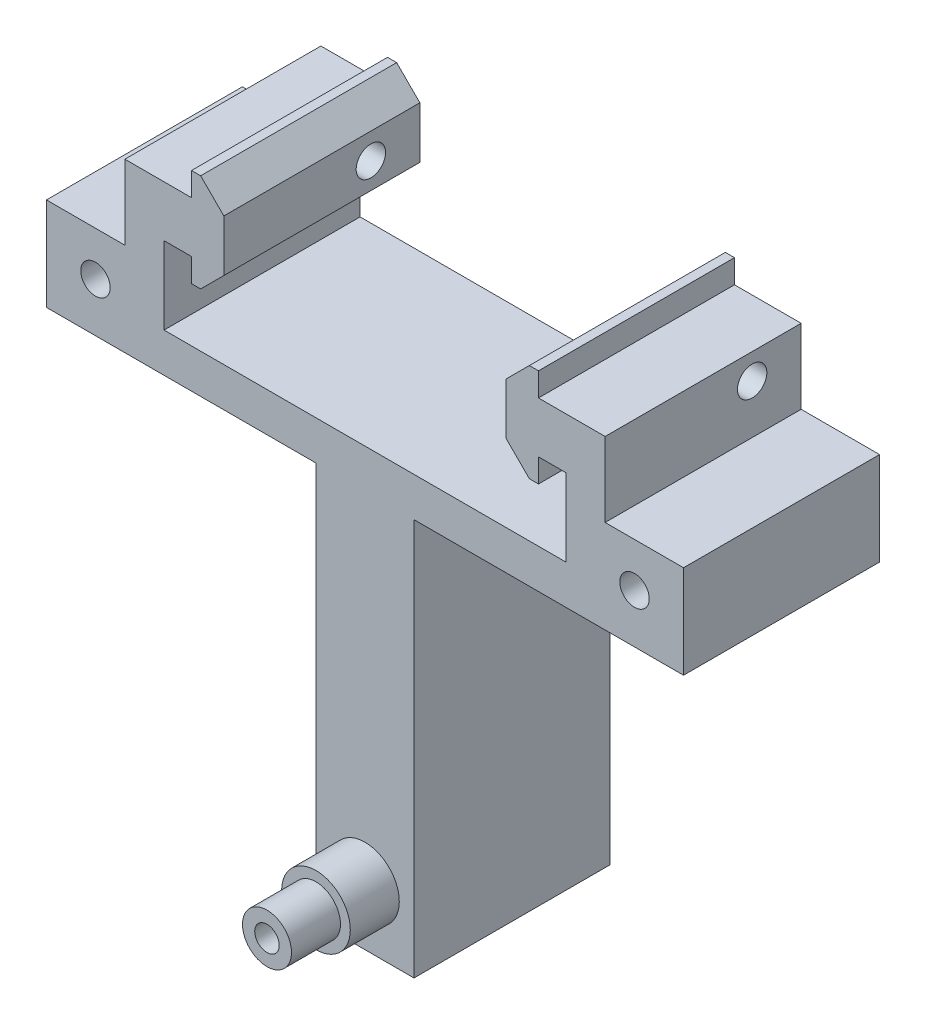
SolidWorks part; units mm, degrees
ref_plane "Front Plane" through (0, 0, 0) normal (0, 0, 1) x (1, 0, 0)
ref_plane "Top Plane" through (0, 0, 0) normal (0, 1, 0) x (1, 0, 0)
ref_plane "Right Plane" through (0, 0, 0) normal (1, 0, 0) x (0, 0, -1)
sketch "Sketch1" plane through (0, 0, 0) normal (0, 0, 1) x (1, 0, 0)
  line L0 (-14.5, 2.6) -> (-7.7, 2.6)
  line L1 (-7.7, 2.6) -> (-7.7, 5)
  line L2 (-7.7, 5) -> (-6.7678, 5)
  line L3 (-6.7678, 5) -> (-4.4, 2.6322)
  line L4 (-4.4, 2.6322) -> (-4.4, -2.6322)
  line L5 (-4.4, -2.6322) -> (-6.7678, -5)
  line L6 (-6.7678, -5) -> (-7.7, -5)
  line L7 (-7.7, -5) -> (-7.7, -2.6)
  line L8 (-7.7, -2.6) -> (-10.5, -2.6)
  line L9 (-10.5, -2.6) -> (-10.5, -10.5)
  line L10 (-10.5, -10.5) -> (30.5, -10.5)
  line L12 (5, -55) -> (15, -55)
  line L16 (-14.5, 2.6) -> (-14.5, -14.5)
  line L17 (-3.9, 2.7565) -> (-3.9, -2.7565) construction
  line L18 (-3.9586, -2.8979) -> (-6.5607, -5.5) construction
  line L19 (-3.9586, 2.8979) -> (-6.5607, 5.5) construction
  line L20 (-6.5607, 5.5) -> (-8, 5.5) construction
  line L21 (-8.2, 5.3) -> (-8.2, 3.1) construction
  line L22 (-8.2, 3.1) -> (-9.3, 3.1) construction
  line L23 (-8.2, -5.3) -> (-8.2, -3.1) construction
  line L24 (-6.5607, -5.5) -> (-8, -5.5) construction
  line L25 (-8.2, -3.1) -> (-9.3, -3.1) construction
  line L26 (-10, -3.8) -> (-10, -8.5) construction
  line L27 (-14.5, -14.5) -> (5, -14.5)
  line L28 (10, 10) -> (10, -10) construction
  line L29 (-8.5, -10) -> (-3.8, -10) construction
  line L30 (5, -14.5) -> (5, -55)
  line L31 (3.8, -10) -> (8.5, -10) construction
  line L34 (8.5, 10) -> (11.5, 10) construction
  line L35 (8.5, -10) -> (11.5, -10) construction
  line L36 (30.5, -2.6) -> (30.5, -10.5)
  line L37 (27.7, -2.6) -> (30.5, -2.6)
  line L38 (27.7, -5) -> (27.7, -2.6)
  line L39 (26.7678, -5) -> (27.7, -5)
  line L40 (24.4, -2.6322) -> (26.7678, -5)
  line L41 (24.4, 2.6322) -> (24.4, -2.6322)
  line L42 (26.7678, 5) -> (24.4, 2.6322)
  line L43 (27.7, 5) -> (26.7678, 5)
  line L44 (27.7, 2.6) -> (27.7, 5)
  line L45 (34.5, 2.6) -> (27.7, 2.6)
  line L46 (34.5, 2.6) -> (34.5, -14.5)
  line L47 (34.5, -14.5) -> (15, -14.5)
  line L48 (15, -14.5) -> (15, -55)
  dimension "D1" = 0.5
  dimension "D2" = 0.5
  dimension "D3" = 0.5
  dimension "D4" = 0.5
  dimension "D5" = 0.5
  dimension "D6" = 0.5
  dimension "D7" = 0.5
  dimension "D8" = 0.5
  dimension "D9" = 0.5
  dimension "D10" = 0.5
  dimension "D11" = 4
  dimension "D12" = 0.5
  dimension "D13" = 4
  dimension "D14" = 5
  dimension "D16" = 45
extrude "Boss-Extrude1" add sketch "Sketch1" along normal blind 20
sketch "Sketch2" plane through (-14.5, 0, 0) normal (-1, 0, 0) x (0, 0, 1)
  line L0 (0, 2.6) -> (0, -14.5) construction
  line L4 (20, -2.6322) -> (20, 2.6322) construction
  circle A0 centre (5, 0) radius 1.5
  point P7 (20, 0)
  dimension "D1" = 5
  dimension "D2" = 3
  dimension "D3" = 0
extrude "Cut-Extrude1" cut sketch "Sketch2" against normal blind 60
sketch "Sketch4" plane through (0, 0, 20) normal (0, 0, 1) x (1, 0, 0)
  line L0 (5, -55) -> (15, -55) construction
  line L1 (30.5, -10.5) -> (-10.5, -10.5) construction
  circle A0 centre (10, -49) radius 2.5
  point P4 (10, -55)
  dimension "D1" = 0
  dimension "D2" = 38.5
  dimension "D3" = 5
extrude "Boss-Extrude2" add sketch "Sketch4" along normal blind 10
sketch "Sketch5" plane through (0, 0, 20) normal (0, 0, 1) x (1, 0, 0)
  circle A1 centre (10, -49) radius 3.5
  dimension "D1" = 7
extrude "Boss-Extrude3" add sketch "Sketch5" along normal blind 5
sketch "Sketch6" plane through (0, 0, 30) normal (0, 0, 1) x (1, 0, 0)
  circle A0 centre (10, -49) radius 1.25
  dimension "D1" = 2.5
extrude "Cut-Extrude3" cut sketch "Sketch6" against normal blind 4
sketch "Sketch7" plane through (-14.5, 0, 0) normal (-1, 0, 0) x (0, 0, 1)
  line L0 (20, 2.6) -> (20, -14.5) construction
  line L1 (0, -14.5) -> (20, -14.5)
  line L2 (0, -14.5) -> (0, -5)
  line L3 (0, -5) -> (20, -5)
  line L4 (20, -14.5) -> (20, -5)
  circle A0 centre (5, 0) radius 1.5 construction
  dimension "D1" = 5
extrude "Boss-Extrude4" add sketch "Sketch7" along normal blind 8
sketch "Sketch8" plane through (34.5, 0, 0) normal (1, 0, 0) x (0, 0, -1)
  line L0 (-20, -14.5) -> (-20, 2.6) construction
  line L1 (0, -14.5) -> (-20, -14.5)
  line L2 (0, -14.5) -> (0, -5)
  line L3 (0, -5) -> (-20, -5)
  line L4 (-20, -14.5) -> (-20, -5)
  circle A0 centre (-5, 0) radius 1.5 construction
  dimension "D1" = 5
extrude "Boss-Extrude5" add sketch "Sketch8" along normal blind 8
sketch "Sketch9" plane through (0, 0, 20) normal (0, 0, 1) x (1, 0, 0)
  line L0 (-22.5, -14.5) -> (-22.5, -5) construction
  line L1 (-22.5, -14.5) -> (5, -14.5) construction
  line L2 (15, -14.5) -> (42.5, -14.5) construction
  line L3 (42.5, -5) -> (42.5, -14.5) construction
  circle A0 centre (-17.5, -9.5) radius 1.5
  circle A1 centre (37.5, -9.5) radius 1.5
  point P10 (33.8368, -9.5)
  dimension "D1" = 3
  dimension "D2" = 5
  dimension "D3" = 5
  dimension "D4" = 5
  dimension "D5" = 3
  dimension "D6" = 5
extrude "Cut-Extrude4" cut sketch "Sketch9" against normal blind 10
